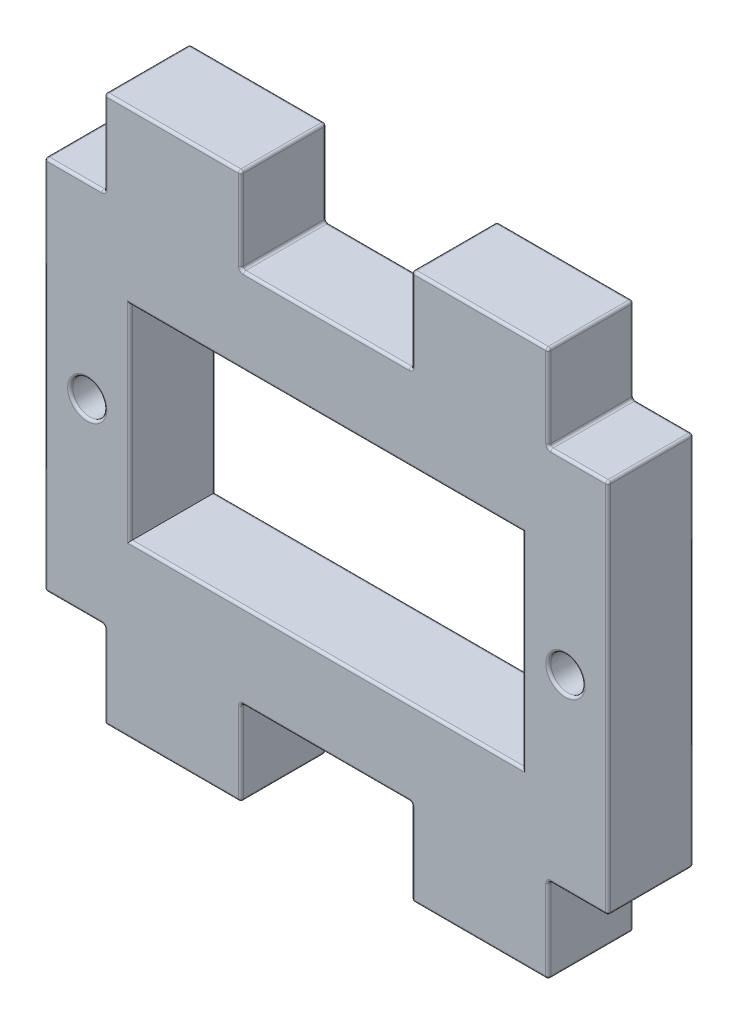
SolidWorks part; units mm, degrees
material "AISI 1020"
ref_plane "Front Plane" through (0, 0, 0) normal (0, 0, 1) x (1, 0, 0)
ref_plane "Top Plane" through (0, 0, 0) normal (0, 1, 0) x (1, 0, 0)
ref_plane "Right Plane" through (0, 0, 0) normal (1, 0, 0) x (0, 0, -1)
sketch "Sketch1" plane through (0, 0, 0) normal (0, 0, 1) x (1, 0, 0)
  line L0 (16.5, 11) -> (-16.5, 11)
  line L1 (11.5, -6) -> (-11.5, -6)
  line L2 (11.5, -6) -> (11.5, 6)
  line L3 (11.5, 6) -> (-11.5, 6)
  line L4 (-11.5, -6) -> (-11.5, 6)
  line L5 (11.5, -6) -> (-11.5, 6) construction
  line L6 (11.5, 6) -> (-11.5, -6) construction
  line L7 (-16.5, -11) -> (-16.5, 11)
  line L8 (16.5, -11) -> (-16.5, -11)
  line L9 (16.5, -11) -> (16.5, 11)
  line L10 (0, 6) -> (0, 0) construction
  line L12 (-13, 11) -> (-13, 16)
  line L13 (-13, 16) -> (-5, 16)
  line L14 (-5, 11) -> (-5, 16)
  line L15 (0, 0) -> (-16.5, 0) construction
  line L16 (5, 11) -> (5, 16)
  line L17 (13, 16) -> (5, 16)
  line L18 (13, 11) -> (13, 16)
  line L19 (13, -11) -> (13, -16)
  line L20 (13, -16) -> (5, -16)
  line L21 (5, -11) -> (5, -16)
  line L22 (-5, -11) -> (-5, -16)
  line L23 (-13, -16) -> (-5, -16)
  line L24 (-13, -11) -> (-13, -16)
  circle A0 centre (-14, 0) radius 1
  circle A1 centre (14, 0) radius 1
  point P0 (0, 0)
  point P29 (-11.5, 0)
  dimension "D7" = 2
  dimension "D1" = 12
  dimension "D2" = 23
  dimension "D4" = 3.5
  dimension "D5" = 5
  dimension "D6" = 8
  dimension "D8" = 2.5
  dimension "D3" = 5
extrude "Boss-Extrude1" add sketch "Sketch1" along normal mid plane 5 contours L8 L9 L0 L7 L1 L4 L3 L2 A0 A1 | L0 L14 L13 L12 | L0 L18 L17 L16 | L8 L24 L23 L22 | L8 L21 L20 L19
fillet "Fillet1" radius 0.15 60 edges at (-13, 16, 0) (-9, 16, -2.5) (-13, 13.5, -2.5) (-9, 16, 2.5) (-5, 16, 0) (-13, 13.5, 2.5) (-13, 11, 0) (-5, 13.5, -2.5) (-14.75, 11, -2.5) (-5, 13.5, 2.5) (-5, 11, 0) (-16.5, 11, 0) (-14.75, 11, 2.5) (0, 11, -2.5) (-16.5, 0, -2.5) (0, 11, 2.5) (5, 11, 0) (-16.5, 0, 2.5) (-16.5, -11, 0) (5, 13.5, -2.5) (-14.75, -11, -2.5) (5, 13.5, 2.5) (5, 16, 0) (-14.75, -11, 2.5) (-13, -11, 0) (9, 16, -2.5) (-13, -13.5, -2.5) (9, 16, 2.5) (13, 16, 0) (-13, -16, 0) (-13, -13.5, 2.5) (13, 13.5, -2.5) (-9, -16, -2.5) (13, 13.5, 2.5) (13, 11, 0) (-5, -16, 0) (-9, -16, 2.5) (14.75, 11, -2.5) (-5, -13.5, -2.5) (14.75, 11, 2.5) (16.5, 11, 0) (-5, -13.5, 2.5) (-5, -11, 0) (16.5, 0, -2.5) (0, -11, -2.5) (16.5, 0, 2.5) (16.5, -11, 0) (0, -11, 2.5) (5, -11, 0) (14.75, -11, -2.5) (5, -13.5, -2.5) (14.75, -11, 2.5) (13, -11, 0) (5, -16, 0) (5, -13.5, 2.5) (13, -13.5, -2.5) (9, -16, -2.5) (13, -13.5, 2.5) (9, -16, 2.5) (13, -16, 0)
fillet "Fillet2" radius 0.15 12 edges at (15, 0, -2.5) (-13, 0, -2.5) (-11.5, 0, -2.5) (0, 6, -2.5) (11.5, 0, -2.5) (0, -6, -2.5) (11.5, 0, 2.5) (0, 6, 2.5) (-11.5, 0, 2.5) (0, -6, 2.5) (-13, 0, 2.5) (15, 0, 2.5)
